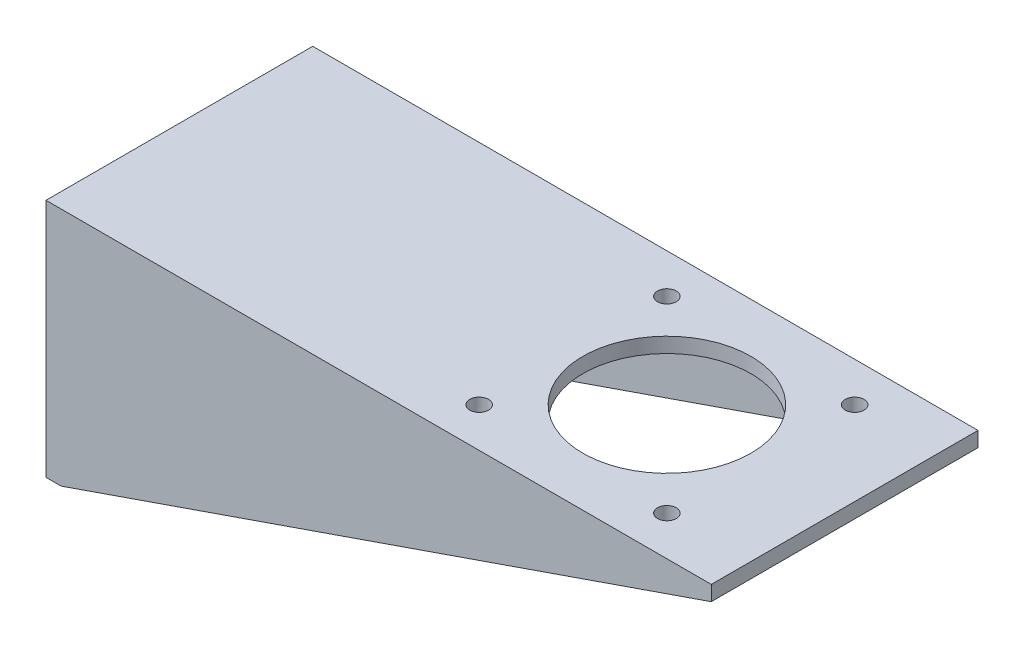
SolidWorks part; units mm, degrees
material "6061-T6 (SS)"
ref_plane "Front Plane" through (0, 0, 0) normal (0, 0, 1) x (1, 0, 0)
ref_plane "Top Plane" through (0, 0, 0) normal (0, 1, 0) x (1, 0, 0)
ref_plane "Right Plane" through (0, 0, 0) normal (1, 0, 0) x (0, 0, -1)
sketch "Sketch1" plane through (0, 0, 0) normal (0, 0, 1) x (1, 0, 0)
  line L0 (0, -15) -> (0, 15)
  line L1 (0, 15) -> (0, 17)
  line L2 (88.7, 17) -> (88.7, 15)
  line L3 (88.7, 15) -> (2, -15)
  line L4 (2, -15) -> (0, -15)
  line L5 (0, 17) -> (2, 17)
  line L6 (2, 17) -> (88.7, 17)
  dimension "D1" = 2
  dimension "D2" = 30
  dimension "D3" = 86.7
extrude "Boss-Extrude1" add sketch "Sketch1" along normal mid plane 35.56
sketch "Sketch2" plane through (0, 0, 0) normal (0, 0, 1) x (1, 0, 0)
  line L0 (2, 15) -> (2, -15)
  line L1 (2, -15) -> (88.7, 15)
  line L2 (88.7, 15) -> (2, 15)
extrude "Cut-Extrude1" cut sketch "Sketch2" against normal offset from surface 1 and the other way offset from surface (16.78 mm away) 1 up to face at (35.88, 3.8, -17.78) other way up to face at (35.88, 3.8, 17.78)
sketch "Sketch4" plane through (2, 0, 0) normal (1, 0, 0) x (0, 0, -1)
  line L1 (0, 0) -> (0, -1) construction
  circle A0 centre (0, -1) radius 8
  point P14 (0, -1)
  dimension "D1" = 16
  dimension "D5" = 1
extrude "Cut-Extrude2" cut sketch "Sketch4" against normal through all
sketch "Sketch5" plane through (0, 15, 0) normal (0, -1, 0) x (1, 0, 0)
  line L0 (2, 0) -> (65, 0) construction
  line L1 (2, -16.78) -> (2, 16.78) construction
  line L2 (2, -16.78) -> (2, 16.78) construction
  circle A0 centre (65, 0) radius 11.2
  point P19 (65, 0)
  dimension "D2" = 22.4
  dimension "D3" = 63
extrude "Cut-Extrude3" cut sketch "Sketch5" against normal through all
sketch "Sketch7" plane through (0, 15, 0) normal (0, -1, 0) x (1, 0, 0)
  line L0 (77.5158, 12.5158) -> (52.4842, 12.5158) construction
  line L1 (52.4842, 12.5158) -> (52.4842, -12.5158) construction
  line L2 (52.4842, -12.5158) -> (77.5158, -12.5158) construction
  line L3 (77.5158, -12.5158) -> (77.5158, 12.5158) construction
  line L4 (49.4842, -12.5158) -> (49.4842, -16.78)
  line L5 (88.7, -16.78) -> (2, -16.78) construction
  line L6 (49.4842, -16.78) -> (55.4842, -16.78)
  line L8 (2, -16.78) -> (88.7, -16.78) construction
  line L9 (55.4842, -16.78) -> (55.4842, -12.5158)
  line L10 (74.5158, -12.5158) -> (74.5158, -16.78)
  line L12 (74.5158, -16.78) -> (80.5158, -16.78)
  line L13 (80.5158, -16.78) -> (80.5158, -12.5158)
  line L14 (80.5158, 12.5158) -> (80.5158, 16.78)
  line L15 (88.7, 16.78) -> (2, 16.78) construction
  line L16 (80.5158, 16.78) -> (74.5158, 16.78)
  line L17 (2, 16.78) -> (88.7, 16.78) construction
  line L18 (74.5158, 16.78) -> (74.5158, 12.5158)
  line L19 (49.4842, 12.5158) -> (49.4842, 16.78)
  line L20 (49.4842, 16.78) -> (55.4842, 16.78)
  line L21 (55.4842, 16.78) -> (55.4842, 12.5158)
  circle A0 centre (65, 0) radius 17.7 construction
  arc A1 (49.4842, 12.5158) -> (55.4842, 12.5158) centre (52.4842, 12.5158) ccw
  arc A2 (55.4842, -12.5158) -> (49.4842, -12.5158) centre (52.4842, -12.5158) ccw
  arc A3 (80.5158, -12.5158) -> (74.5158, -12.5158) centre (77.5158, -12.5158) ccw
  arc A4 (74.5158, 12.5158) -> (80.5158, 12.5158) centre (77.5158, 12.5158) ccw
  dimension "D1" = 35.4
  dimension "D2" = 6
extrude "Boss-Extrude2" add sketch "Sketch7" along normal blind 2
sketch "Sketch10" plane through (0, 13, 0) normal (0, -1, 0) x (1, 0, 0)
  point P0 (52.4842, 12.5158)
  point P1 (77.5158, 12.5158)
  point P3 (77.5158, -12.5158)
  point P5 (52.4842, -12.5158)
hole_wizard "M3x0.5 Tapped Hole2" positions "Sketch12" profile "Sketch11" tap size "M3x0.5" standard "ANSI Metric"
sketch "Sketch12" plane through (0, 13, 0) normal (0, -1, 0) x (-1, 0, 0)
  point P0 (-52.4842, -12.5158)
  point P3 (-77.5158, -12.5158)
  point P6 (-77.5158, 12.5158)
  point P9 (-52.4842, 12.5158)
sketch "Sketch11" plane through (52.4842, 13, 12.5158) normal (1, 0, 0) x (0, 0, -1)
  line L0 (0, 0) -> (0, 8.2511)
  line L1 (0, 8.2511) -> (1.25, 7.5)
  line L2 (1.25, 7.5) -> (1.25, 0)
  line L5 (1.25, 0) -> (0, 0)
  line L10 (0, 8.2511) -> (-1.25, 7.5) construction
  line L11 (0, -6.35) -> (0, 107.95) construction
  dimension "Tap Drill Dia." = 2.5
  dimension "Tap Drill Depth" = 7.5
  dimension "Drill Angle" = 118
fillet "Fillet6" radius 2 10 edges at (2, 0, -16.78) (2, 0, 16.78) (80.5158, 14, -16.78) (74.5158, 14, -16.78) (55.4842, 14, -16.78) (49.4842, 14, -16.78) (49.4842, 14, 16.78) (74.5158, 14, 16.78) (55.4842, 14, 16.78) (80.5158, 14, 16.78)
sketch "Sketch13" plane through (0, 0, 0) normal (-1, 0, 0) x (0, 0, 1)
  line L0 (10, -1) -> (0, -11) construction
  line L1 (0, -11) -> (-10, -1) construction
  line L2 (-10, -1) -> (0, 9) construction
  line L3 (0, 9) -> (10, -1) construction
  line L4 (10, -1) -> (0, -1) construction
  line L5 (0, -1) -> (0, -11) construction
  line L6 (-10, -1) -> (0, -1) construction
  line L7 (0, -1) -> (0, 9) construction
  dimension "D1" = 10
  dimension "D2" = 1
hole_wizard "M3 Clearance Hole1" positions "Sketch15" profile "Sketch14" hole size "M3" standard "ANSI Metric"
sketch "Sketch15" plane through (0, 0, 0) normal (-1, 0, 0) x (0, 0, 1)
  point P0 (0, 9)
  point P3 (10, -1)
  point P6 (0, -11)
  point P9 (-10, -1)
sketch "Sketch14" plane through (0, 9, 0) normal (0, 1, 0) x (0, 0, 1)
  line L0 (0, 0) -> (0, 12.7)
  line L1 (0, 12.7) -> (1.7, 12.7)
  line L2 (1.7, 12.7) -> (1.7, 0)
  line L5 (1.7, 0) -> (0, 0)
  line L10 (0, 12.7) -> (-1.7, 12.7) construction
  line L11 (0, -6.35) -> (0, 107.95) construction
  dimension "Hole Dia." = 3.4
  dimension "Hole Depth" = 12.7
  dimension "Drill Angle" = 180
